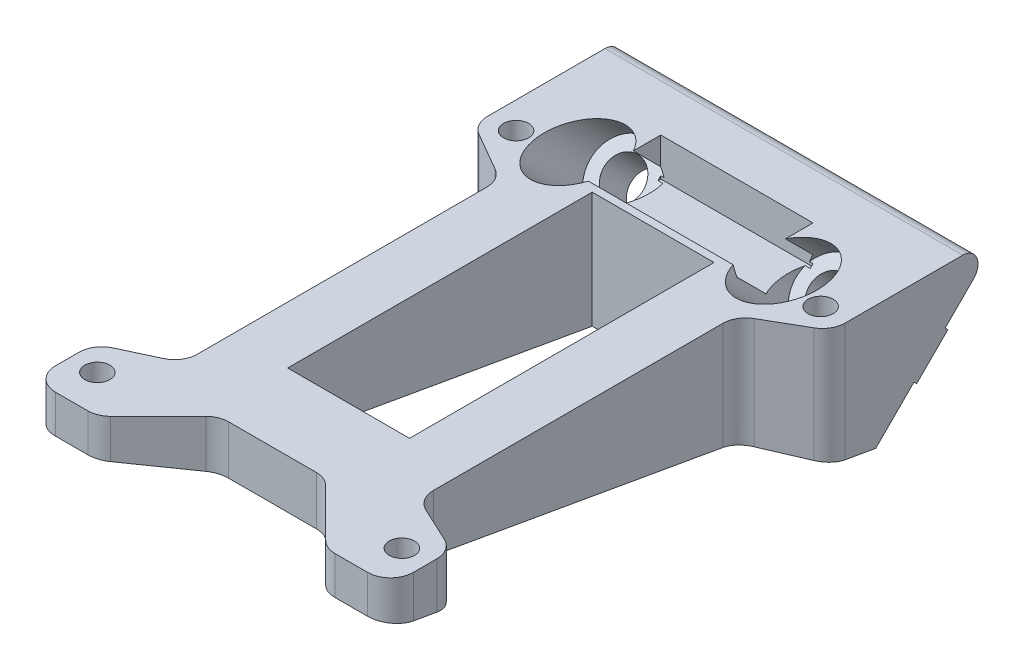
SolidWorks part; units mm, degrees
ref_plane "前视基准面" through (0, 0, 0) normal (0, 0, 1) x (1, 0, 0)
ref_plane "上视基准面" through (0, 0, 0) normal (0, 1, 0) x (1, 0, 0)
ref_plane "右视基准面" through (0, 0, 0) normal (1, 0, 0) x (0, 0, -1)
sketch "草图2" plane through (0, 0, 0) normal (0, 1, 0) x (1, 0, 0)
  line L0 (0, 0) -> (23.5, 0)
  line L1 (23.5, 0) -> (23.5, -19)
  line L4 (23.5, -80) -> (0, -80)
  line L5 (0, -80) -> (0, 0)
  line L6 (23.5, -19) -> (23.5, -80)
  dimension "D1" = 23.5
  dimension "D2" = 80
  dimension "D3" = 23.5
  dimension "D4" = 23.5
  dimension "D6" = 61
extrude "凸台-拉伸2" add sketch "草图2" along normal blind 5
mirror "镜向1" about plane through (0, 5, 80) normal (1, 0, 0) of "凸台-拉伸2"
sketch "草图5" plane through (0, 0, 0) normal (1, 0, 0) x (0, 0, -1)
  line L2 (-16.2635, -11.2635) -> (0, 5)
  line L7 (-7.1418, -2.1418) -> (-11.243, -6.243)
  line L8 (-7.1418, -2.1418) -> (-6.7882, -2.4953)
  line L9 (-11.243, -6.243) -> (-10.8894, -6.5966)
  line L10 (-6.7882, -2.4953) -> (-10.8894, -6.5966)
  line L11 (-8.8388, -4.5459) -> (-14.0224, 0.6377) construction
  line L12 (-80, 5) -> (0, 5) construction
  line L13 (-80, 0) -> (-16.2635, -11.2635)
  line L14 (-80, 0) -> (0, 0) construction
  line L15 (-80, 0) -> (0, 0)
  dimension "D1" = 23
  dimension "D2" = 10
  dimension "D3" = 45
  dimension "D5" = 5.8
  dimension "D6" = 0.5
extrude "凸台-拉伸3" add sketch "草图5" along normal mid plane 47
sketch "草图3" plane through (0, 5, 0) normal (0, 1, 0) x (1, 0, 0)
  line L0 (-41.875, -20) -> (42.0058, -20) construction
  line L1 (-48.5488, -75) -> (45.2773, -75) construction
  line L2 (-20, 7.7517) -> (-20, -80.1072) construction
  line L3 (20, 7.7517) -> (20, -77.5947) construction
  line L4 (-23.5, -80) -> (23.5, -80) construction
  circle A0 centre (-20, -20) radius 1.65
  circle A1 centre (20, -20) radius 1.65
  circle A2 centre (-20, -75) radius 1.65
  circle A3 centre (20, -75) radius 1.65
  point P10 (0, -80)
  dimension "D5" = 3.3
  dimension "D1" = 5
  dimension "D2" = 55
  dimension "D3" = 40
  dimension "D4" = 20
extrude "切除-拉伸1" cut sketch "草图3" against normal through all
sketch "草图8" plane through (0, 5, 0) normal (0, -1, 0) x (1, 0, 0)
  circle A0 centre (-20, 20) radius 3
  circle A1 centre (20, 20) radius 3
  circle A2 centre (20, 75) radius 3
  circle A3 centre (-20, 75) radius 3
  dimension "D1" = 6
extrude "切除-拉伸5" cut sketch "草图8" along normal up to next from offset 3 contours A0 | A1
sketch "草图12" plane through (0, 5, 0) normal (0, 1, 0) x (1, 0, 0)
  circle A1 centre (-20, -75) radius 3
  circle A2 centre (-20, -75) radius 3
  circle A3 centre (20, -75) radius 3
  circle A4 centre (20, -75) radius 3
  circle A5 centre (20, -20) radius 3
  circle A6 centre (20, -20) radius 3
  circle A7 centre (-20, -20) radius 3
  circle A8 centre (-20, -20) radius 3
  dimension "D1" = 0
  dimension "D2" = 0
  dimension "D3" = 0
  dimension "D4" = 0
extrude "切除-拉伸10" cut sketch "草图12" against normal up to next from offset 3 contours A2 | A4 offset against normal yes
sketch "草图4" plane through (0, 5, 0) normal (0, 1, 0) x (1, 0, 0)
  line L0 (-23.5, -80) -> (23.5, -80) construction
  line L1 (-10, -11) -> (10, -11)
  line L2 (-10, -11) -> (-10, -21)
  line L3 (-10, -21) -> (10, -21)
  line L4 (10, -11) -> (10, -21)
  line L5 (-15, -80) -> (-7, -72)
  line L6 (-7, -72) -> (7, -72)
  line L7 (7, -72) -> (15, -80)
  line L8 (15, -80) -> (-15, -80)
  line L9 (-23.5, -72) -> (-15.5, -68.2695)
  line L10 (-23.5, -80) -> (-23.5, 0) construction
  line L11 (-15.5, -68.2695) -> (-15.5, -26.6188)
  line L12 (-15.5, -26.6188) -> (-23.5, -22)
  line L13 (-23.5, -22) -> (-23.5, -72)
  line L14 (-23.5, -80) -> (23.5, -80) construction
  line L15 (23.5, 0) -> (-23.5, 0) construction
  line L16 (0, 0) -> (0, -5.79) construction
  line L17 (15.5, -26.6188) -> (23.5, -22)
  line L18 (15.5, -68.2695) -> (15.5, -26.6188)
  line L19 (23.5, -72) -> (15.5, -68.2695)
  line L20 (23.5, -22) -> (23.5, -72)
  line L21 (23.5, 0) -> (-23.5, 0) construction
  point P6 (0, -80)
  point P10 (0, -80)
  dimension "D2" = 10
  dimension "D3" = 20
  dimension "D4" = 10
  dimension "D5" = 30
  dimension "D6" = 8
  dimension "D7" = 45
  dimension "D8" = 45
  dimension "D9" = 8
  dimension "D10" = 22
  dimension "D11" = 8
  dimension "D12" = 65
  dimension "D13" = 60
  dimension "D14" = 11
extrude "切除-拉伸2" cut sketch "草图4" against normal blind 5 contours L4 L1 L2 L3
sketch "草图10" plane through (0, 5, 0) normal (0, 1, 0) x (1, 0, 0)
  line L1 (-8, -22) -> (8, -22)
  line L2 (-8, -22) -> (-8, -62)
  line L3 (-8, -62) -> (8, -62)
  line L4 (-7, -72) -> (-15, -80)
  line L5 (7, -72) -> (-7, -72)
  line L6 (15, -80) -> (7, -72)
  line L7 (-15, -80) -> (15, -80)
  line L8 (-7, -72) -> (-15, -80)
  line L9 (7, -72) -> (-7, -72)
  line L10 (15, -80) -> (7, -72)
  line L11 (-15, -80) -> (15, -80)
  line L12 (8, -22) -> (8, -62)
  line L20 (23.5, -22) -> (15.5, -26.6188)
  line L21 (23.5, -72) -> (23.5, -22)
  line L22 (15.5, -68.2695) -> (23.5, -72)
  line L23 (15.5, -26.6188) -> (15.5, -68.2695)
  line L24 (23.5, -22) -> (15.5, -26.6188)
  line L25 (23.5, -72) -> (23.5, -22)
  line L26 (15.5, -68.2695) -> (23.5, -72)
  line L27 (15.5, -26.6188) -> (15.5, -68.2695)
  line L28 (-15.5, -26.6188) -> (-23.5, -22)
  line L29 (-23.5, -22) -> (-23.5, -72)
  line L30 (-23.5, -72) -> (-15.5, -68.2695)
  line L31 (-15.5, -68.2695) -> (-15.5, -26.6188)
  line L32 (-15.5, -26.6188) -> (-23.5, -22)
  line L33 (-23.5, -22) -> (-23.5, -72)
  line L34 (-23.5, -72) -> (-15.5, -68.2695)
  line L35 (-15.5, -68.2695) -> (-15.5, -26.6188)
  point P2 (0, -80)
  dimension "D2" = 16
  dimension "D5" = 40
  dimension "D6" = 18
  dimension "D7" = 8
  dimension "D1" = 0
  dimension "D3" = 0
  dimension "D4" = 0
extrude "切除-拉伸11" cut sketch "草图10" against normal through all
fillet "圆角1" radius 3 14 edges at (-23.5, -2.6248, 22) (-23.5, 1.7931, 72) (23.5, 1.7931, 72) (23.5, -2.6248, 22) (15, 2.5, 80) (-15, 2.5, 80) (-15.5, -2.2167, 26.6188) (-15.5, 1.4635, 68.2695) (15.5, 1.4635, 68.2695) (15.5, -2.2167, 26.6188) (-7, 1.7931, 72) (7, 1.7931, 72) (-23.5, 2.5, 80) (23.5, 2.5, 80)
sketch "草图9" plane through (23.5, 0, 0) normal (1, 0, 0) x (0, 0, -1)
  line L0 (-5, 0) -> (0, 5)
  line L1 (-5, 0) -> (0, 0) construction
  line L2 (0, 5) -> (0, 0) construction
  line L3 (-5, 0) -> (0, 0)
  line L4 (0, 5) -> (0, 0)
extrude "切除-拉伸6" cut sketch "草图9" against normal through all
sketch "草图6" plane through (0, 2.1464, 2.1464) normal (0, -0.7071, -0.7071) x (1, 0, 0)
  line L0 (-23.5, 9.4645) -> (23.5, 9.4645) construction
  line L1 (-23.5, 6.5645) -> (-23.5, 12.3645) construction
  line L2 (23.5, 6.5645) -> (23.5, 12.3645) construction
  line L3 (-13.5, 12.3645) -> (-13.5, 6.5645) construction
  line L4 (23.5, 12.3645) -> (-23.5, 12.3645) construction
  line L5 (23.5, 6.5645) -> (-23.5, 6.5645) construction
  line L6 (13.5, 12.3645) -> (13.5, 6.5645) construction
  line L7 (23.5, 12.3645) -> (-23.5, 12.3645) construction
  line L8 (23.5, 6.5645) -> (-23.5, 6.5645) construction
  circle A0 centre (-13.5, 9.4645) radius 2.6
  circle A1 centre (13.5, 9.4645) radius 2.6
  dimension "D3" = 5.2
  dimension "D1" = 10
  dimension "D2" = 10
extrude "切除-拉伸3" cut sketch "草图6" against normal through all
sketch "草图7" plane through (0, 2.1464, 2.1464) normal (0, -0.7071, -0.7071) x (1, 0, 0)
  circle A0 centre (-13.5, 9.4645) radius 4.4
  circle A1 centre (13.5, 9.4645) radius 4.4
  dimension "D1" = 8.8
extrude "切除-拉伸4" cut sketch "草图7" against normal up to next from offset 5 offset against normal yes
fillet "圆角3" radius 2 1 edges at (0, 5, 0)
